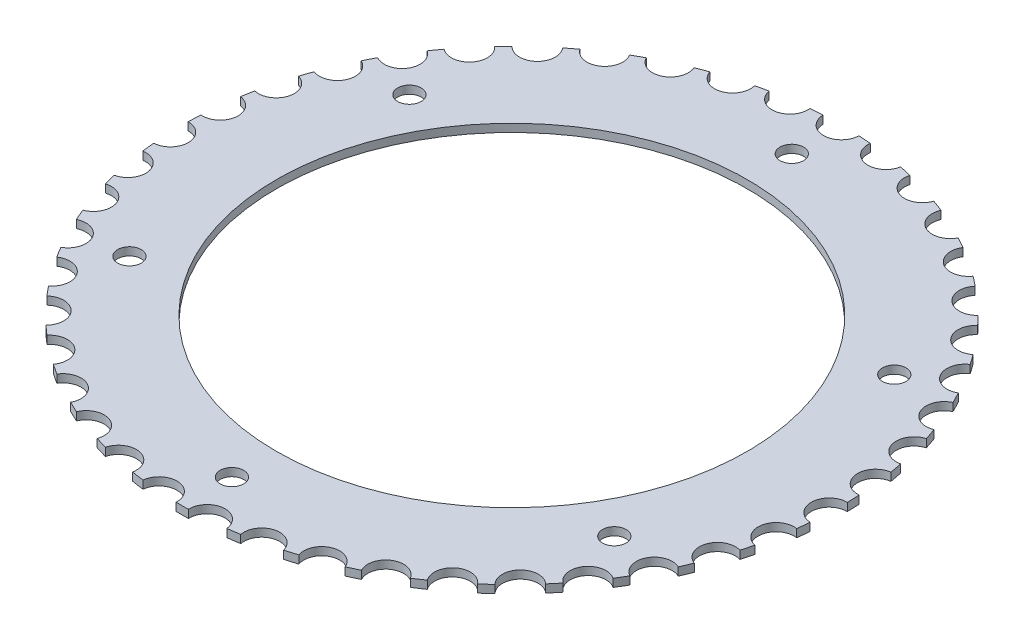
SolidWorks part; units mm, degrees
ref_plane "Front Plane" through (0, 0, 0) normal (0, 0, 1) x (1, 0, 0)
ref_plane "Top Plane" through (0, 0, 0) normal (0, 1, 0) x (1, 0, 0)
ref_plane "Right Plane" through (0, 0, 0) normal (1, 0, 0) x (0, 0, -1)
sketch "Sketch1" plane through (0, 0, 0) normal (0, 1, 0) x (1, 0, 0)
  circle A0 centre (0, 0) radius 70
  circle A1 centre (0, 0) radius 50
  dimension "D1" = 140
extrude "Boss-Extrude1" add sketch "Sketch1" along normal blind 1.7
sketch "Sketch3" plane through (0, 1.7, 0) normal (0, 1, 0) x (1, 0, 0)
  line L0 (0, 0) -> (0, 70) construction
  circle A0 centre (0, 70) radius 3.81
  circle A1 centre (0, 0) radius 70 construction
  point P7 (0, 70.778)
extrude "Cut-Extrude1" cut sketch "Sketch3" against normal blind 2.54
sketch "Sketch4" plane through (0, 0, 0) normal (0, 1, 0) x (1, 0, 0)
  point P0 (0, 0)
pattern_circular "CirPattern1" count 43 over 360 about axis through (0, 0, 0) along (0, 1, 0) of "Cut-Extrude1"
sketch "Sketch5" plane through (0, 0, 0) normal (0, -1, 0) x (-1, 0, 0)
  circle A0 centre (0, 0) radius 59.45 construction
  circle A1 centre (0, 59.45) radius 2.5
  circle A2 centre (51.4852, 29.725) radius 2.5
  circle A3 centre (51.4852, -29.725) radius 2.5
  circle A4 centre (0, -59.45) radius 2.5
  circle A5 centre (-51.4852, -29.725) radius 2.5
  circle A6 centre (-51.4852, 29.725) radius 2.5
  point P17 (0, 0)
  dimension "D1" = 5
  dimension "D2" = 6
extrude "Cut-Extrude2" cut sketch "Sketch5" against normal blind 10
